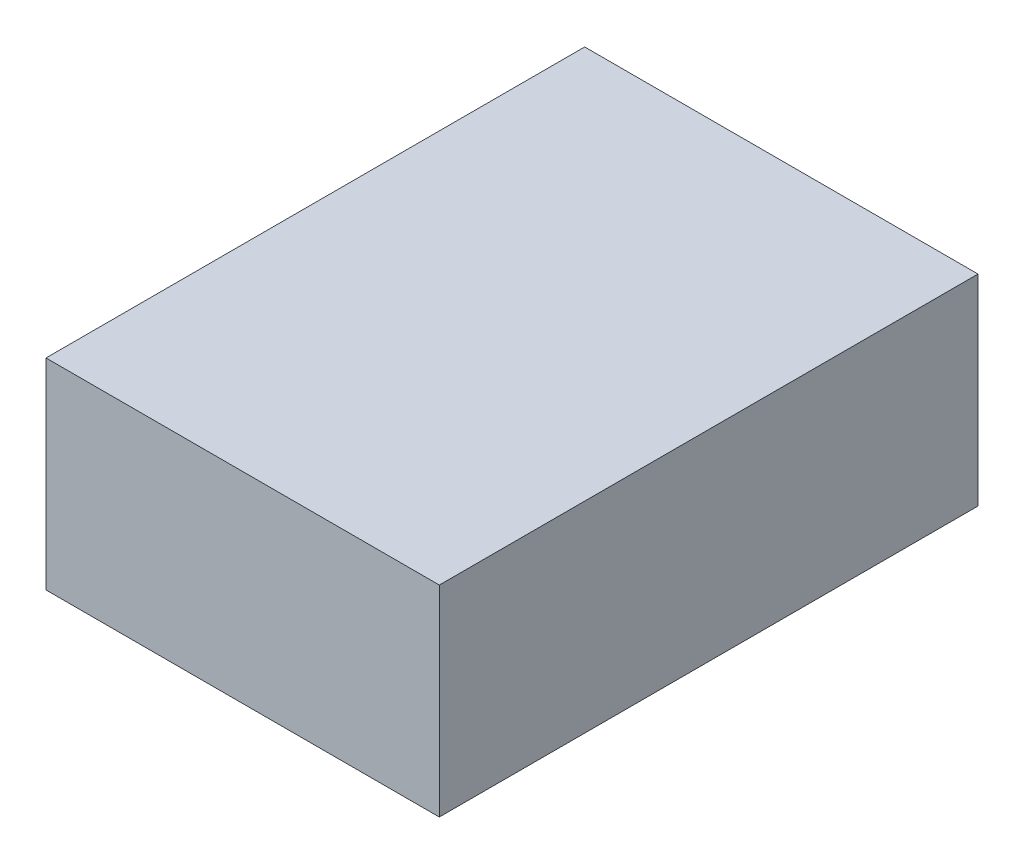
SolidWorks part; units mm, degrees
ref_plane "Front Plane" through (0, 0, 0) normal (0, 0, 1) x (1, 0, 0)
ref_plane "Top Plane" through (0, 0, 0) normal (0, 1, 0) x (1, 0, 0)
ref_plane "Right Plane" through (0, 0, 0) normal (1, 0, 0) x (0, 0, -1)
sketch "Sketch1" plane through (0, 0, 0) normal (0, 1, 0) x (1, 0, 0)
  line L1 (-23, 31.5) -> (23, 31.5)
  line L2 (-23, 31.5) -> (-23, -31.5)
  line L3 (-23, -31.5) -> (23, -31.5)
  line L4 (23, 31.5) -> (23, -31.5)
  point P4 (-23, 0)
  point P6 (0, 31.5)
  dimension "D1" = 63
  dimension "D2" = 46
extrude "Boss-Extrude1" add sketch "Sketch1" along normal blind 23.5
